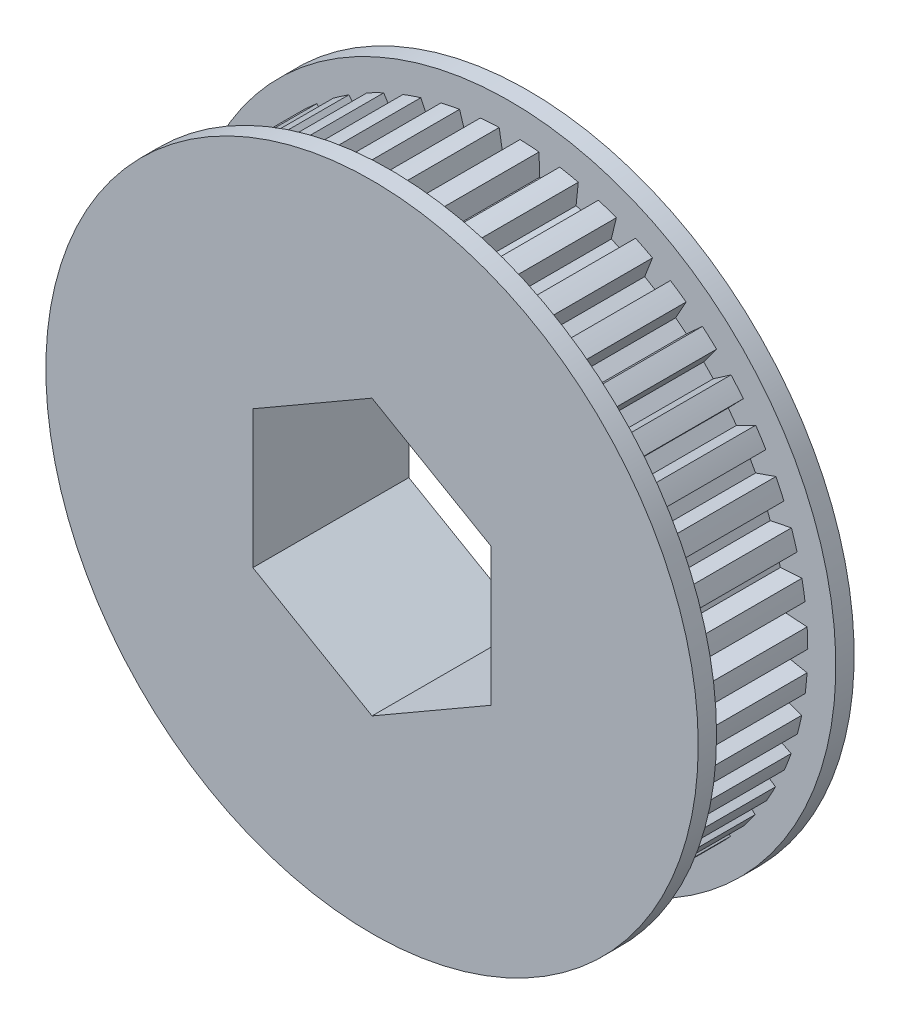
SolidWorks part; units mm, degrees
ref_plane "Front Plane" through (0, 0, 0) normal (0, 0, 1) x (1, 0, 0)
ref_plane "Top Plane" through (0, 0, 0) normal (0, 1, 0) x (1, 0, 0)
ref_plane "Right Plane" through (0, 0, 0) normal (1, 0, 0) x (0, 0, -1)
sketch "Sketch3" plane through (0, 0, 0) normal (0, 0, 1) x (1, 0, 0)
  circle A0 centre (0, 0) radius 16.25
  dimension "D1" = 32.5
extrude "Boss-Extrude2" add sketch "Sketch3" along normal mid plane 6.5
sketch "Sketch1" plane through (0, 0, 0) normal (0, 0, 1) x (1, 0, 0)
  line L0 (-0.375, 15.08) -> (0.375, 15.08)
  line L2 (-0.375, 15.08) -> (-0.6543, 16.7561)
  line L3 (-0.6543, 16.7561) -> (0.6543, 16.7561)
  line L4 (0.6543, 16.7561) -> (0.375, 15.08)
  line L5 (-0.5, 15.83) -> (0.5, 15.83) construction
  point P9 (0, 16.7561)
  point P10 (0, 15.08)
  dimension "D1" = 0.75
  dimension "D2" = 0.75
  dimension "D3" = 1
  dimension "D4" = 15.08
extrude "Cut-Extrude2" cut sketch "Sketch1" against normal through all both and the other way through all
pattern_circular "CirPattern3" count 47 over 360 about axis through (0, 0, 0) along (0, 0, 1) of "Cut-Extrude2"
sketch "Sketch5" plane through (0, 0, -3.25) normal (0, 0, -1) x (-1, 0, 0)
  circle A0 centre (0, 0) radius 17.78
  dimension "D1" = 35.56
extrude "Boss-Extrude3" add sketch "Sketch5" along normal blind 1
sketch "Sketch6" plane through (0, 0, 3.25) normal (0, 0, 1) x (1, 0, 0)
  circle A0 centre (0, 0) radius 17.78
  dimension "D1" = 35.56
extrude "Boss-Extrude4" add sketch "Sketch6" along normal blind 1
sketch "Sketch7" plane through (0, 0, 4.25) normal (0, 0, 1) x (1, 0, 0)
  line L1 (0, 7.5) -> (-6.4952, 3.75)
  line L2 (-6.4952, 3.75) -> (-6.4952, -3.75)
  line L3 (-6.4952, -3.75) -> (0, -7.5)
  line L4 (0, -7.5) -> (6.4952, -3.75)
  line L5 (6.4952, -3.75) -> (6.4952, 3.75)
  line L6 (6.4952, 3.75) -> (0, 7.5)
  circle A0 centre (0, 0) radius 6.4952 construction
  dimension "D1" = 15
extrude "Cut-Extrude3" cut sketch "Sketch7" against normal through all both and the other way through all
